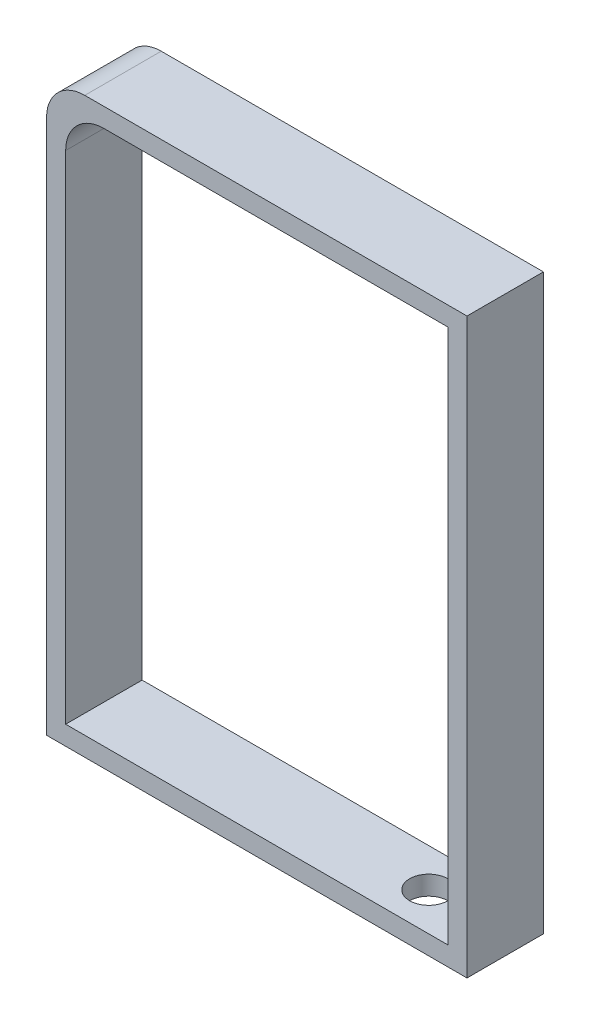
SolidWorks part; units mm, degrees
ref_plane "前视基准面" through (0, 0, 0) normal (0, 0, 1) x (1, 0, 0)
ref_plane "上视基准面" through (0, 0, 0) normal (0, 1, 0) x (1, 0, 0)
ref_plane "右视基准面" through (0, 0, 0) normal (1, 0, 0) x (0, 0, -1)
sketch "草图1" plane through (0, 0, 0) normal (0, 0, 1) x (1, 0, 0)
  line L1 (-27.5, -37.5) -> (27.5, -37.5)
  line L2 (-27.5, -37.5) -> (-27.5, 37.5)
  line L3 (-27.5, 37.5) -> (27.5, 37.5)
  line L4 (27.5, -37.5) -> (27.5, 37.5)
  line L5 (-27.5, -37.5) -> (27.5, 37.5) construction
  line L6 (-27.5, 37.5) -> (27.5, -37.5) construction
  point P0 (0, 0)
  dimension "D1" = 55
  dimension "D2" = 75
extrude "凸台-拉伸1" add sketch "草图1" along normal blind 10
sketch "草图3" plane through (0, 0, 0) normal (0, 0, -1) x (-1, 0, 0)
  line L0 (27.5, -37.5) -> (-27.5, -37.5) construction
  line L1 (-25, 35) -> (25, 35)
  line L2 (-25, 35) -> (-25, -35)
  line L3 (-25, -35) -> (25, -35)
  line L4 (25, 35) -> (25, -35)
  line L5 (-25, 35) -> (25, -35) construction
  line L6 (-25, -35) -> (25, 35) construction
  line L7 (27.5, 37.5) -> (27.5, -37.5) construction
  point P0 (0, 0)
  dimension "D1" = 70
  dimension "D2" = 50
  dimension "D3" = 2.5
  dimension "D4" = 2.5
extrude "切除-拉伸1" cut sketch "草图3" against normal through all
fillet "圆角2" radius 5 2 edges at (-27.5, 37.5, 5) (-25, 35, 5)
sketch "草图4" plane through (0, 35, 0) normal (0, -1, 0) x (1, 0, 0)
  line L0 (-27.5, 0) -> (27.5, 0) construction
  line L1 (27.5, 10) -> (27.5, 0) construction
  circle A0 centre (17.5, 5) radius 2.5
  dimension "D2" = 5
  dimension "D3" = 10
  dimension "D1" = 5
extrude "切除-拉伸2" cut sketch "草图4" against normal blind 1.5
sketch "草图5" plane through (0, -35, 0) normal (0, 1, 0) x (1, 0, 0)
  circle A0 centre (17.5, -5) radius 2.5 construction
  circle A1 centre (17.5, -5) radius 2.5
extrude "切除-拉伸3" cut sketch "草图5" against normal through all
